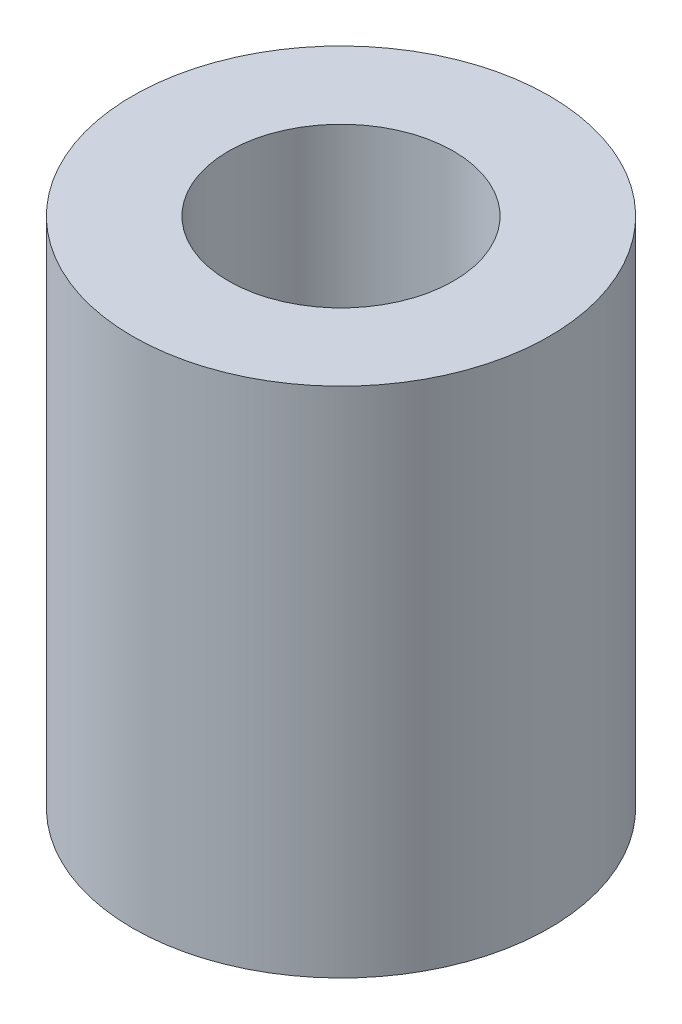
SolidWorks part; units mm, degrees
ref_plane "Front Plane" through (0, 0, 0) normal (0, 0, 1) x (1, 0, 0)
ref_plane "Top Plane" through (0, 0, 0) normal (0, 1, 0) x (1, 0, 0)
ref_plane "Right Plane" through (0, 0, 0) normal (1, 0, 0) x (0, 0, -1)
sketch "Sketch1" plane through (0, 0, 0) normal (0, 1, 0) x (1, 0, 0)
  circle A0 centre (0, 0) radius 3.429
  circle A1 centre (0, 0) radius 6.35
  dimension "D1" = 6.858
  dimension "D2" = 12.7
extrude "Boss-Extrude1" add sketch "Sketch1" along normal blind 15.621
equation "\"tightTol\" = 0.005in"
equation "\"normTol\"= 0.01in"
equation "\"looseTol\"= 0.02in"
equation "\"D1@Sketch1\"=\"looseTol\"+0.25"
equation "\"D1@Boss-Extrude1\"=0.625in-\"normTol\""
